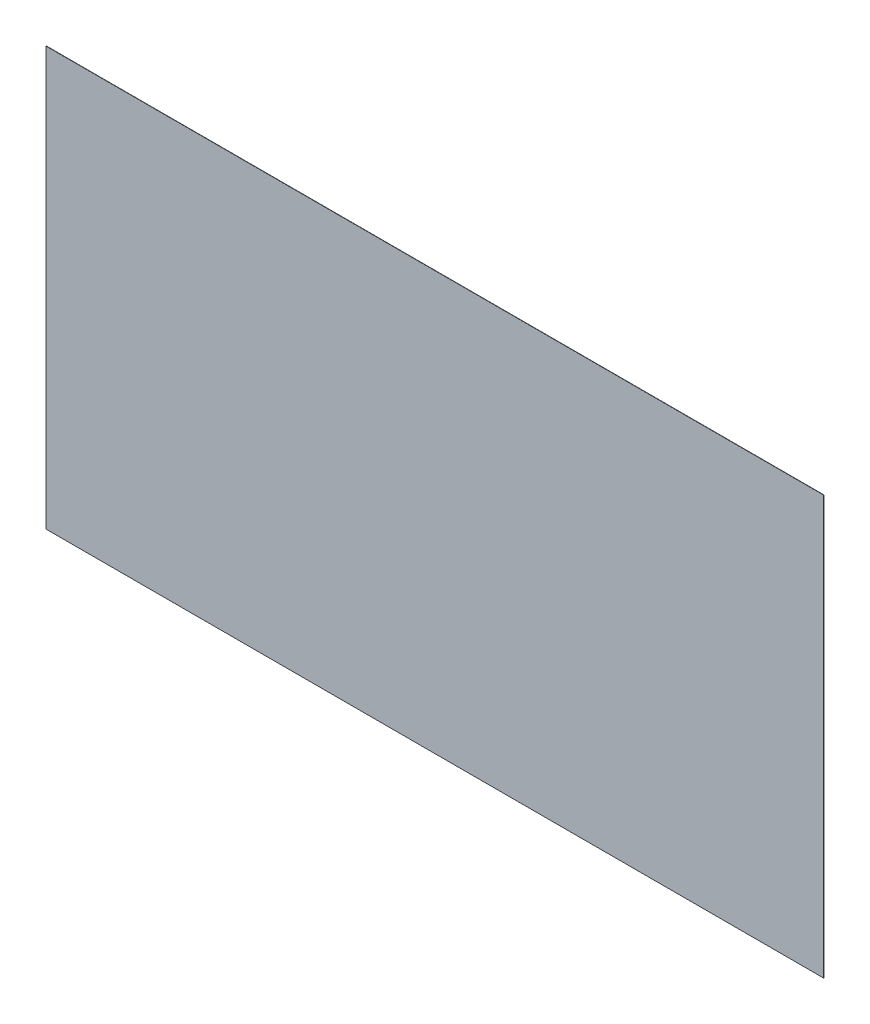
SolidWorks part; units mm, degrees
material "PVC 0.007 Plasticized"
ref_plane "Front Plane" through (0, 0, 0) normal (0, 0, 1) x (1, 0, 0)
ref_plane "Top Plane" through (0, 0, 0) normal (0, 1, 0) x (1, 0, 0)
ref_plane "Right Plane" through (0, 0, 0) normal (1, 0, 0) x (0, 0, -1)
sketch "Sketch1" plane through (0, 0, 0) normal (0, 0, 1) x (1, 0, 0)
  line L1 (-1050, -565) -> (1050, -565)
  line L2 (-1050, -565) -> (-1050, 565)
  line L3 (-1050, 565) -> (1050, 565)
  line L4 (1050, -565) -> (1050, 565)
  line L5 (-1050, -565) -> (1050, 565) construction
  line L6 (-1050, 565) -> (1050, -565) construction
  point P0 (0, 0)
  dimension "D1" = 2100
  dimension "D2" = 1130
extrude "Boss-Extrude1" add sketch "Sketch1" along normal blind 0.9
shell "Shell1" thickness 0.35
